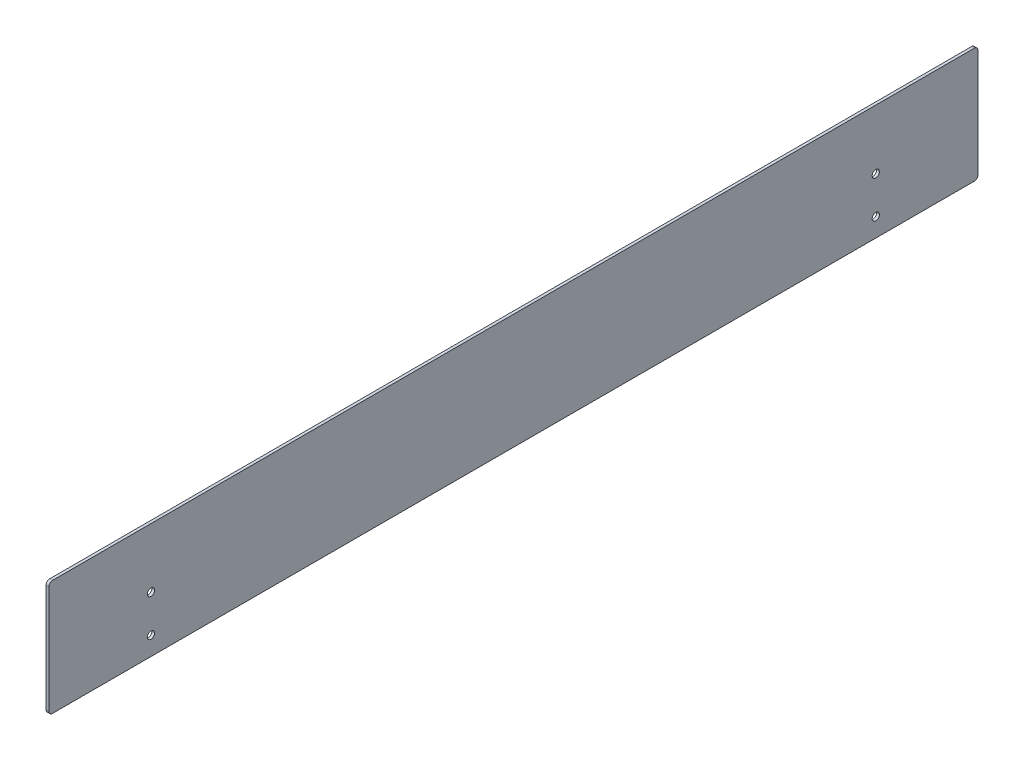
SolidWorks part; units mm, degrees
ref_plane "Front Plane" through (0, 0, 0) normal (0, 0, 1) x (1, 0, 0)
ref_plane "Top Plane" through (0, 0, 0) normal (0, 1, 0) x (1, 0, 0)
ref_plane "Right Plane" through (0, 0, 0) normal (1, 0, 0) x (0, 0, -1)
sketch "Sketch1" plane through (0, 0, 0) normal (1, 0, 0) x (0, 0, -1)
  line L1 (-286.3393, -78.2926) -> (213.6607, -78.2926)
  line L2 (-286.3393, -78.2926) -> (-286.3393, -140.2926)
  line L3 (-286.3393, -140.2926) -> (213.6607, -140.2926)
  line L4 (213.6607, -78.2926) -> (213.6607, -140.2926)
  circle A0 centre (158.6607, -110.2926) radius 1.95
  circle A1 centre (158.6607, -130.2926) radius 1.95
  circle A2 centre (-231.3393, -110.2926) radius 1.95
  circle A3 centre (-231.3393, -130.2926) radius 1.95
  point P12 (0, 0)
  point P13 (0, 0)
  dimension "D3" = 55
  dimension "D1" = 500
  dimension "D2" = 62
  dimension "D4" = 20
  dimension "D5" = 10
  dimension "D6" = 55
  dimension "D7" = 20
  dimension "D8" = 10
extrude "Boss-Extrude1" add sketch "Sketch1" along normal blind 1.5
fillet "Fillet1" radius 2 4 edges at (0.75, -140.2926, -213.6607) (0.75, -78.2926, -213.6607) (0.75, -140.2926, 286.3393) (0.75, -78.2926, 286.3393)
